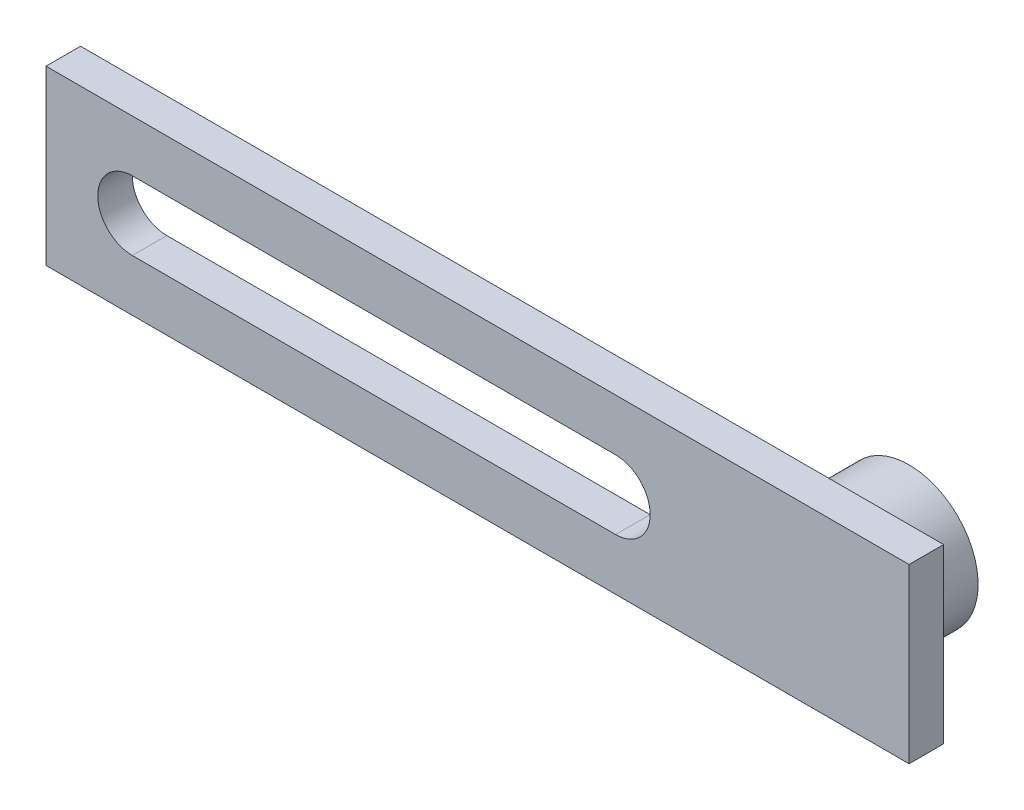
SolidWorks part; units mm, degrees
ref_plane "Front Plane" through (0, 0, 0) normal (0, 0, 1) x (1, 0, 0)
ref_plane "Top Plane" through (0, 0, 0) normal (0, 1, 0) x (1, 0, 0)
ref_plane "Right Plane" through (0, 0, 0) normal (1, 0, 0) x (0, 0, -1)
sketch "Sketch1" plane through (0, 0, 0) normal (0, 0, 1) x (1, 0, 0)
  line L0 (-112.5, -12.5) -> (-42.5, -12.5) construction
  line L1 (0, 0) -> (-125, 0)
  line L2 (0, 0) -> (0, -25)
  line L3 (0, -25) -> (-125, -25)
  line L4 (-125, 0) -> (-125, -25)
  line L5 (-112.5, -7.5) -> (-42.5, -7.5)
  line L6 (-112.5, -17.5) -> (-42.5, -17.5)
  arc A0 (-112.5, -7.5) -> (-112.5, -17.5) centre (-112.5, -12.5) ccw
  arc A1 (-42.5, -17.5) -> (-42.5, -7.5) centre (-42.5, -12.5) ccw
  point P7 (-77.5, -12.5)
  dimension "D1" = 125
  dimension "D2" = 25
  dimension "D3" = 10
  dimension "D4" = 12.5
  dimension "D5" = 12.5
  dimension "D6" = 70
extrude "Boss-Extrude1" add sketch "Sketch1" along normal blind 5
sketch "Sketch2" plane through (0, 0, 0) normal (0, 0, -1) x (-1, 0, 0)
  line L0 (0, -25) -> (0, 0) construction
  line L1 (0, 0) -> (125, 0) construction
  circle A0 centre (15, -12.5) radius 10
  dimension "D1" = 20
  dimension "D2" = 15
  dimension "D3" = 12.5
extrude "Boss-Extrude2" add sketch "Sketch2" along normal blind 5
sketch "Sketch3" plane through (0, 0, -5) normal (0, 0, -1) x (-1, 0, 0)
  circle A0 centre (15, -12.5) radius 10
  circle A1 centre (15, -12.5) radius 5
  dimension "D1" = 20
  dimension "D2" = 10
extrude "Boss-Extrude3" add sketch "Sketch3" along normal blind 5
